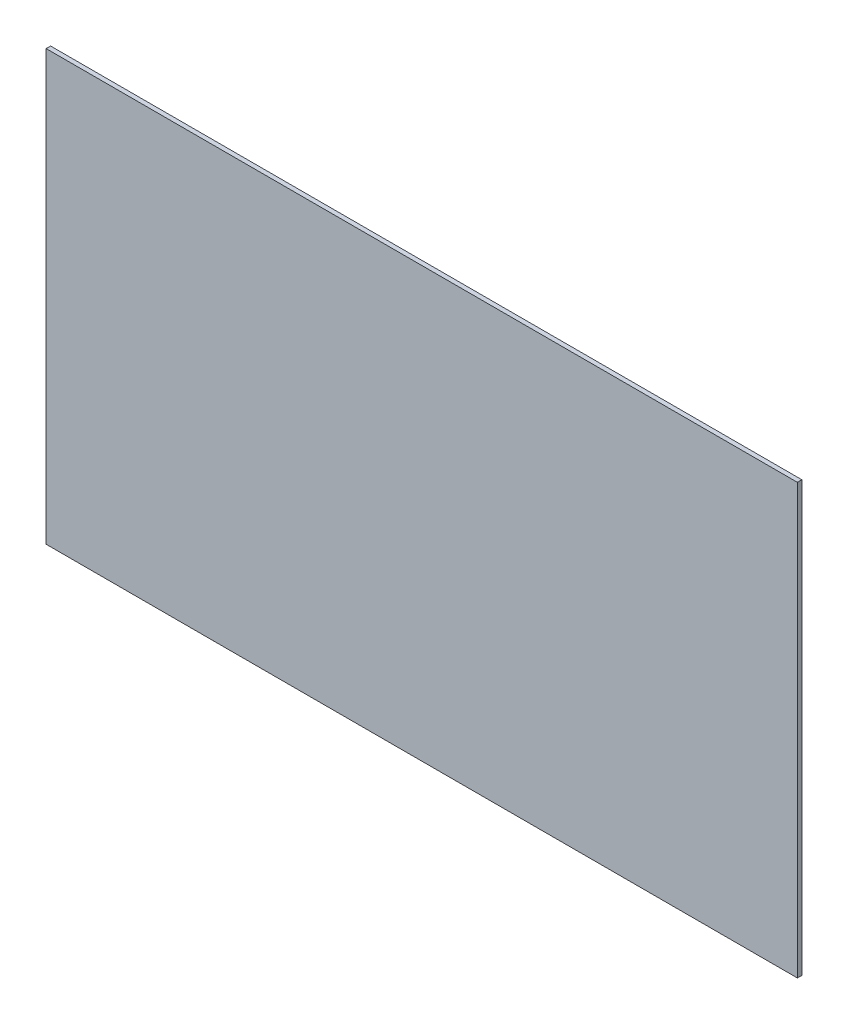
SolidWorks part; units mm, degrees
ref_plane "Alzado" through (0, 0, 0) normal (0, 0, 1) x (1, 0, 0)
ref_plane "Planta" through (0, 0, 0) normal (0, 1, 0) x (1, 0, 0)
ref_plane "Vista lateral" through (0, 0, 0) normal (1, 0, 0) x (0, 0, -1)
sketch "Croquis1" plane through (0, 0, 0) normal (0, 0, 1) x (1, 0, 0)
  line L1 (0, 0) -> (533.4, 0)
  line L2 (0, 0) -> (0, 304.8)
  line L3 (0, 304.8) -> (533.4, 304.8)
  line L4 (533.4, 0) -> (533.4, 304.8)
  dimension "D1" = 533.4
  dimension "D2" = 304.8
extrude "Saliente-Extruir1" add sketch "Croquis1" along normal blind 3.175
